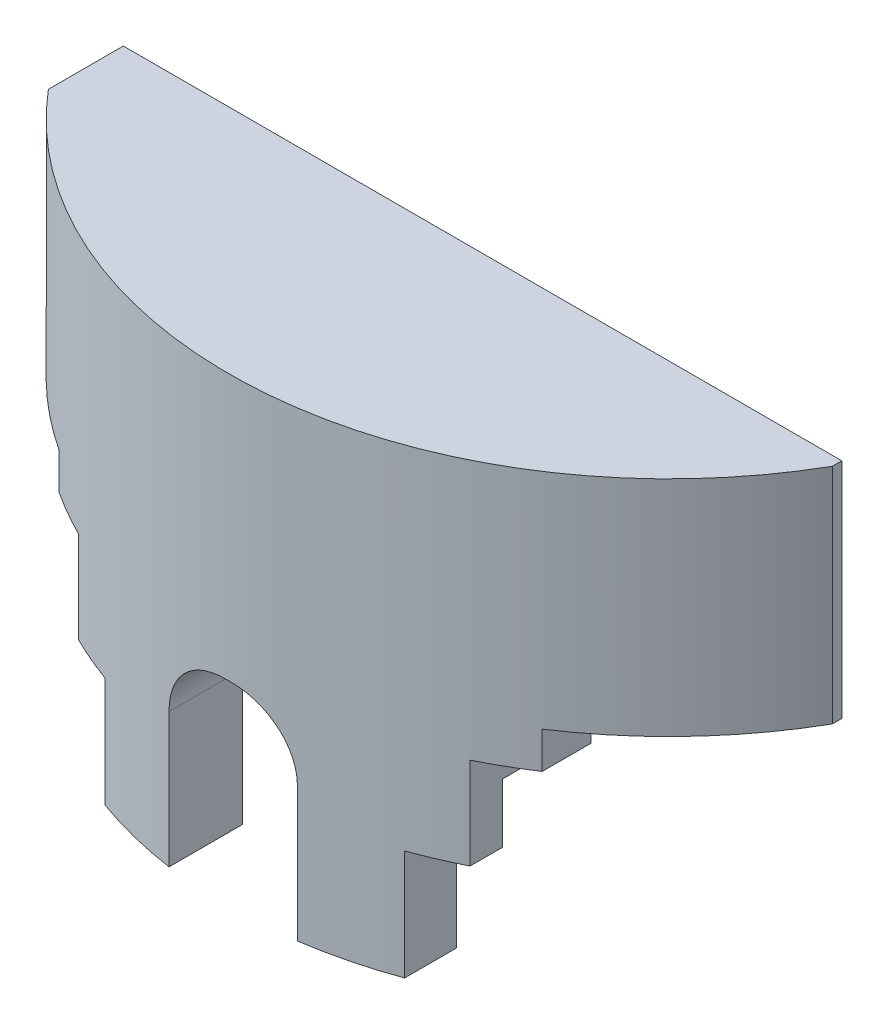
SolidWorks part; units mm, degrees
material "Pure Lead"
ref_plane "Front Plane" through (0, 0, 0) normal (0, 0, 1) x (1, 0, 0)
ref_plane "Top Plane" through (0, 0, 0) normal (0, 1, 0) x (1, 0, 0)
ref_plane "Right Plane" through (0, 0, 0) normal (1, 0, 0) x (0, 0, -1)
sketch "Sketch1" plane through (0, 0, 0) normal (0, 1, 0) x (1, 0, 0)
  line L0 (-62.5, -34.2) -> (-62.5, -35.7456)
  line L1 (-62.5, -34.2) -> (62.5, -34.2)
  line L2 (62.5, -34.2) -> (62.5, -35.7456)
  arc A0 (-62.5, -35.7456) -> (62.5, -35.7456) centre (0, 0) ccw
  dimension "D1" = 144
  dimension "D2" = 125
  dimension "D3" = 34.2
extrude "Boss-Extrude1" add sketch "Sketch1" against normal blind 36.5
sketch "Sketch2" plane through (0, -36.5, 0) normal (0, -1, 0) x (1, 0, 0)
  line L0 (-39.5, 60.1976) -> (-39.5, 34.2)
  line L1 (62.5, 34.2) -> (-62.5, 34.2) construction
  line L2 (-39.5, 34.2) -> (39.5, 34.2)
  line L3 (39.5, 34.2) -> (39.5, 60.1976)
  arc A0 (62.5, 35.7456) -> (-62.5, 35.7456) centre (0, 0) ccw construction
  arc A1 (-39.5, 60.1976) -> (39.5, 60.1976) centre (0, 0) cw
  line M2 (-62.5, 34.2) -> (62.5, 34.2)
  arc M4 (62.5, 35.7456) -> (-62.5, 35.7456) centre (0, 0) ccw
  dimension "D1" = 79
extrude "Boss-Extrude2" add sketch "Sketch2" along normal blind 6 contours L3 L0 M2 M4
sketch "Sketch3" plane through (0, -42.5, 0) normal (0, -1, 0) x (1, 0, 0)
  line L0 (-32, 64.4981) -> (-32, 34.2)
  line L1 (-39.5, 34.2) -> (39.5, 34.2) construction
  line L2 (-32, 34.2) -> (32, 34.2)
  line L3 (32, 34.2) -> (32, 64.4981)
  arc A0 (39.5, 60.1976) -> (-39.5, 60.1976) centre (0, 0) ccw construction
  arc A1 (32, 64.4981) -> (-32, 64.4981) centre (0, 0) ccw
  dimension "D1" = 64
extrude "Boss-Extrude3" add sketch "Sketch3" along normal blind 15
sketch "Sketch4" plane through (0, -57.5, 0) normal (0, -1, 0) x (1, 0, 0)
  line L0 (-24.5, 34.2) -> (-24.5, 67.7034)
  line L1 (-32, 34.2) -> (32, 34.2) construction
  line L2 (-24.5, 34.2) -> (24.5, 34.2)
  line L3 (24.5, 34.2) -> (24.5, 67.7034)
  arc A0 (32, 64.4981) -> (-32, 64.4981) centre (0, 0) ccw construction
  arc A1 (-24.5, 67.7034) -> (24.5, 67.7034) centre (0, 0) cw
  dimension "D1" = 49
extrude "Boss-Extrude4" add sketch "Sketch4" along normal blind 18
sketch "Sketch7" plane through (0, 0, 34.2) normal (0, 0, -1) x (-1, 0, 0)
  line L0 (0, -75.5) -> (0, -53.5) construction
  line L1 (24.5, -75.5) -> (-24.5, -75.5) construction
  line L2 (-32.5, -53.5) -> (-32.5, -86)
  line L3 (-32.5, -86) -> (32.5, -86)
  line L4 (32.5, -86) -> (32.5, -53.5)
  arc A0 (32.5, -53.5) -> (-32.5, -53.5) centre (0, -53.5) ccw
  dimension "D2" = 65
  dimension "D1" = 22
extrude "Cut-Extrude2" cut sketch "Sketch7" against normal blind 25
sketch "Sketch5" plane through (0, -75.5, 0) normal (0, -1, 0) x (1, 0, 0)
  line L0 (-24.5, 34.2) -> (24.5, 34.2) construction
  line L1 (-10.5, 34.2) -> (10.5, 34.2)
  line L2 (-10.5, 34.2) -> (-10.5, 72)
  line L3 (-10.5, 72) -> (10.5, 72)
  line L4 (10.5, 34.2) -> (10.5, 72)
  arc A0 (24.5, 67.7034) -> (-24.5, 67.7034) centre (0, 0) ccw construction
  point P6 (0, 72)
  point P10 (0, 72)
  dimension "D1" = 21
extrude "Cut-Extrude1" cut sketch "Sketch5" against normal blind 32
fillet "Fillet1" radius 10 2 edges at (-10.5, -43.5, 65.2151) (10.5, -43.5, 65.2151)
sketch "Sketch8" plane through (0, 0, 34.2) normal (0, 0, -1) x (-1, 0, 0)
  line L0 (-27, -22) -> (27, -22) construction
  line L1 (-27, -2) -> (27, -2)
  line L2 (-27, -42) -> (27, -42)
  line L3 (-62.5, 0) -> (62.5, 0) construction
  arc A0 (-27, -2) -> (-27, -42) centre (-27, -22) ccw
  arc A1 (27, -42) -> (27, -2) centre (27, -22) ccw
  point P2 (0, -22)
  point P10 (0, 0)
  dimension "D3" = 20
  dimension "D1" = 22
  dimension "D2" = 54
extrude "Cut-Extrude3" cut sketch "Sketch8" against normal blind 18
sketch "Sketch9" plane through (0, 0, 34.2) normal (0, 0, -1) x (-1, 0, 0)
  line L1 (-40.775, -36.5) -> (40.775, -36.5)
  line L2 (-40.775, -36.5) -> (-40.775, -56.5)
  line L3 (-40.775, -56.5) -> (40.775, -56.5)
  line L4 (40.775, -36.5) -> (40.775, -56.5)
  dimension "D1" = 20
extrude "Cut-Extrude4" cut sketch "Sketch9" against normal up to surface (18 mm away) up to face at (0, -27.9799, 52.2)
sketch "Sketch10" plane through (0, 0, 34.2) normal (0, 0, -1) x (-1, 0, 0)
  line L0 (-62.5, 0) -> (62.5, 0) construction
  line L1 (55, 0) -> (62.5, 0)
  line L2 (55, 0) -> (55, -36.5)
  line L3 (55, -36.5) -> (62.5, -36.5)
  line L4 (62.5, 0) -> (62.5, -36.5)
  point P7 (0, 0)
  dimension "D1" = 55
extrude "Cut-Extrude6" cut sketch "Sketch10" against normal through all
equation "\"smallPulleyTeeth\"= 30"
equation "\"largePulleyTeeth\"= 30"
equation "\"eighthThick\"= 3.0mm"
equation "\"sixteenthThick\" = 1.7mm"
equation "\"quarterThick\"=6.0mm"
equation "\"OD\" = 145mm"
equation "\"puckAngle\" = 60.5deg"
equation "\"puckDiam\" = 76.5mm"
equation "\"puckDist\" = 85mm"
equation "\"scoopFillet\" = 5mm"
equation "\"axlePress\" = 5.9mm"
equation "\"press\" = 0.2mm"
equation "\"wheelClear\" = 0.3mm"
equation "\"10-32clear\" = 4.8mm"
equation "\"10-32tap\" = 4.45mm"
equation "\"6-32clear\" = 3.3mm"
equation "\"8-32clear\" = 4.0mm"
equation "\"4-40clear\" = 3.0mm"
equation "\"wheelHeight\" = 22mm"
equation "\"wheelWell\" = 65mm"
equation "\"ledSmall\" = 3.1mm"
equation "\"ledLarge\" = 4.2mm"
equation "\"ledLength\" = 4.2mm"
equation "\"4-40close\" = 2.7mm"
equation "\"4-40nutThick\" = 2.2mm"
equation "\"4-40nutWidth\" = 6.2mm"
equation "\"4-40insertHeight\" = 3.5mm"
equation "\"4-40insert\" = 4.25mm"
equation "\"D1@Sketch1\"=\"OD\"-1"
